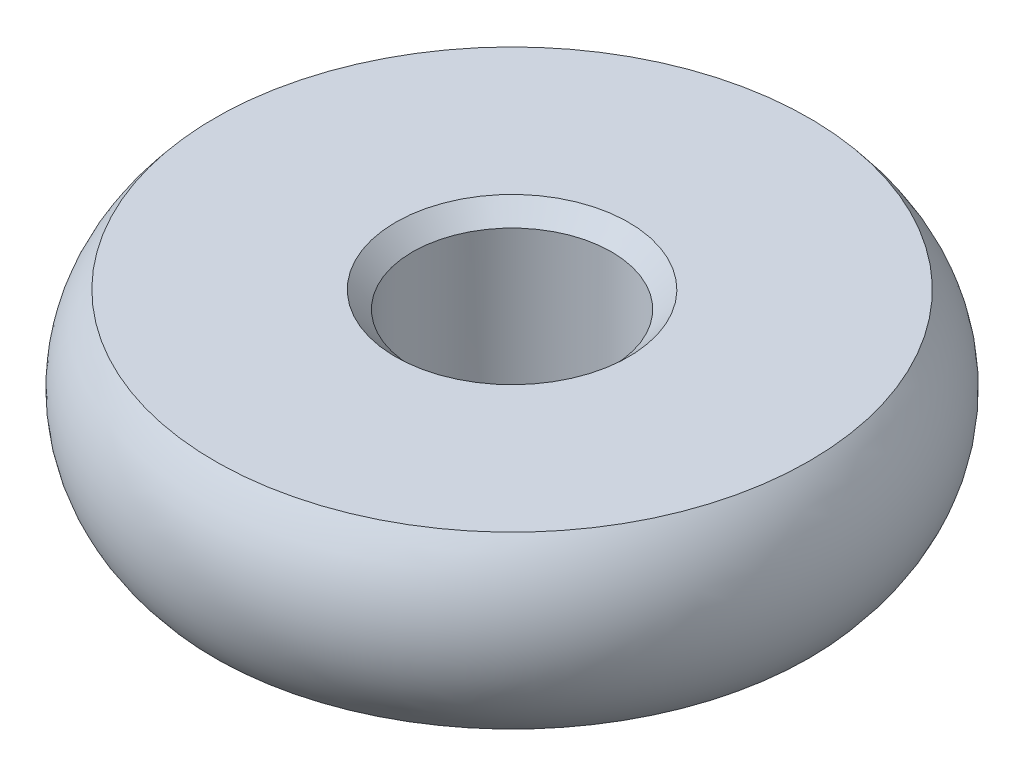
SolidWorks part; units mm, degrees
material "Custom Plastic"
ref_plane "Front Plane" through (0, 0, 0) normal (0, 0, 1) x (1, 0, 0)
ref_plane "Top Plane" through (0, 0, 0) normal (0, 1, 0) x (1, 0, 0)
ref_plane "Right Plane" through (0, 0, 0) normal (1, 0, 0) x (0, 0, -1)
sketch "Sketch1" plane through (0, 0, 0) normal (0, 0, 1) x (1, 0, 0)
  line L0 (0, -562.8227) -> (0, 27578.3136) construction
  line L1 (17.5, 15) -> (17.5, -15)
  line L2 (17.5, -15) -> (52.2705, -15)
  line L3 (17.5, 15) -> (52.2705, 15)
  arc A0 (52.2705, 15) -> (52.2705, -15) centre (35.5, 0) cw
  point P5 (17.5, 0)
  point P9 (58, 0)
  dimension "D3" = 22.5
  dimension "D1" = 30
  dimension "D2" = 17.5
  dimension "D4" = 116
revolve "Revolve1" add sketch "Sketch1" angle 360 about L0
chamfer "Chamfer1" distance 3 angle 45 2 edges at (17.5, 15, 0) (17.5, -15, 0)
